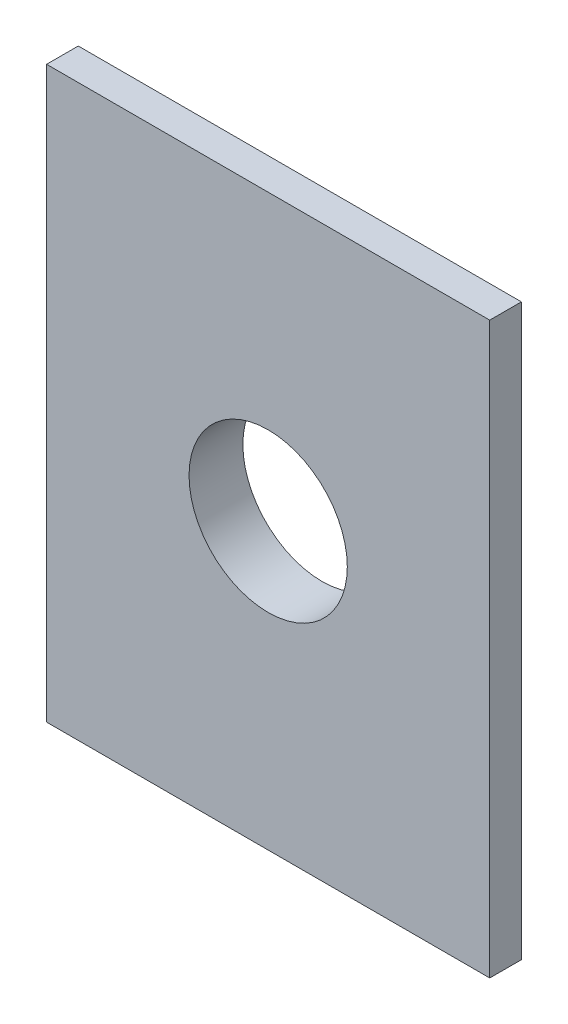
SolidWorks part; units mm, degrees
ref_plane "Alzado" through (0, 0, 0) normal (0, 0, 1) x (1, 0, 0)
ref_plane "Planta" through (0, 0, 0) normal (0, 1, 0) x (1, 0, 0)
ref_plane "Vista lateral" through (0, 0, 0) normal (1, 0, 0) x (0, 0, -1)
sketch "Croquis1" plane through (0, 0, 0) normal (0, 0, 1) x (1, 0, 0)
  line L0 (0, 0) -> (140, 0)
  line L1 (140, 0) -> (140, 180)
  line L2 (140, 180) -> (0, 180)
  line L3 (0, 180) -> (0, 49.1777)
  line L5 (140, 180) -> (0, 0) construction
  line L6 (0, 180) -> (140, 0) construction
  line L7 (0, 49.1777) -> (0, 0)
  circle A1 centre (70, 90) radius 35
  dimension "D3" = 140
  dimension "D1" = 140
  dimension "D2" = 180
extrude "Saliente-Extruir1" add sketch "Croquis1" along normal blind 10
sketch "Croquis2" plane through (0, 0, 0) normal (0, 0, -1) x (-1, 0, 0)
  circle A0 centre (-70, 90) radius 35
  circle A1 centre (-70, 90) radius 25
extrude "Saliente-Extruir2" add sketch "Croquis2" along normal blind 7 separate body
sketch "Croquis3" plane through (0, 0, 10) normal (0, 0, 1) x (1, 0, 0)
  circle A0 centre (70, 90) radius 35
  circle A1 centre (70, 90) radius 25
extrude "Saliente-Extruir4" add sketch "Croquis3" against normal up to surface (10 mm away) up to face at (35, 90, 0)
